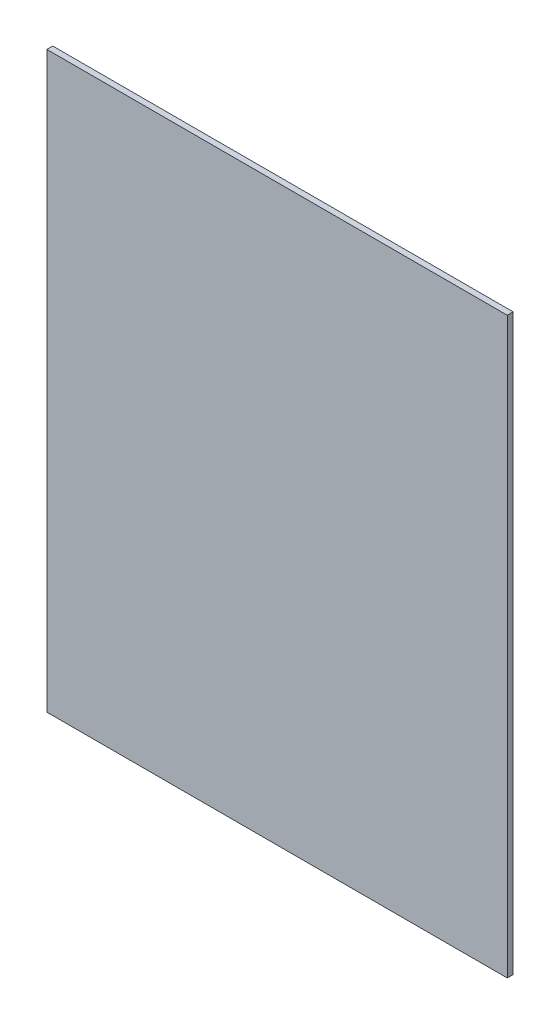
SolidWorks part; units mm, degrees
ref_plane "Front Plane" through (0, 0, 0) normal (0, 0, 1) x (1, 0, 0)
ref_plane "Top Plane" through (0, 0, 0) normal (0, 1, 0) x (1, 0, 0)
ref_plane "Right Plane" through (0, 0, 0) normal (1, 0, 0) x (0, 0, -1)
sketch "Sketch1" plane through (0, 0, 0) normal (0, 0, 1) x (1, 0, 0)
  line L1 (-117.1575, 146.05) -> (117.1575, 146.05)
  line L2 (-117.1575, 146.05) -> (-117.1575, -146.05)
  line L3 (-117.1575, -146.05) -> (117.1575, -146.05)
  line L4 (117.1575, 146.05) -> (117.1575, -146.05)
  line L5 (-117.1575, 146.05) -> (117.1575, -146.05) construction
  line L6 (-117.1575, -146.05) -> (117.1575, 146.05) construction
  point P0 (0, 0)
  dimension "D1" = 234.315
  dimension "D2" = 292.1
extrude "Boss-Extrude1" add sketch "Sketch1" along normal blind 2.9972
